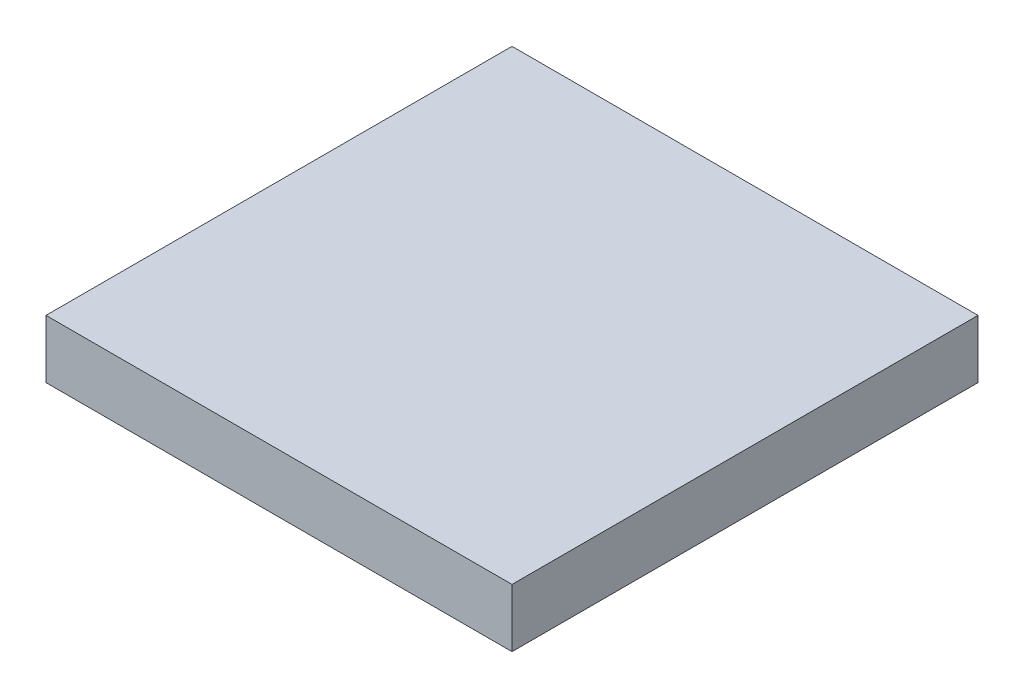
SolidWorks part; units mm, degrees
ref_plane "Front Plane" through (0, 0, 0) normal (0, 0, 1) x (1, 0, 0)
ref_plane "Top Plane" through (0, 0, 0) normal (0, 1, 0) x (1, 0, 0)
ref_plane "Right Plane" through (0, 0, 0) normal (1, 0, 0) x (0, 0, -1)
sketch "Sketch1" plane through (0, 0, 0) normal (0, 1, 0) x (1, 0, 0)
  line L1 (-100, 200) -> (100, 200)
  line L2 (-100, 200) -> (-100, 0)
  line L3 (-100, 0) -> (100, 0)
  line L4 (100, 200) -> (100, 0)
  point P4 (0, 0)
  dimension "D1" = 200
extrude "Boss-Extrude1" add sketch "Sketch1" along normal blind 25
